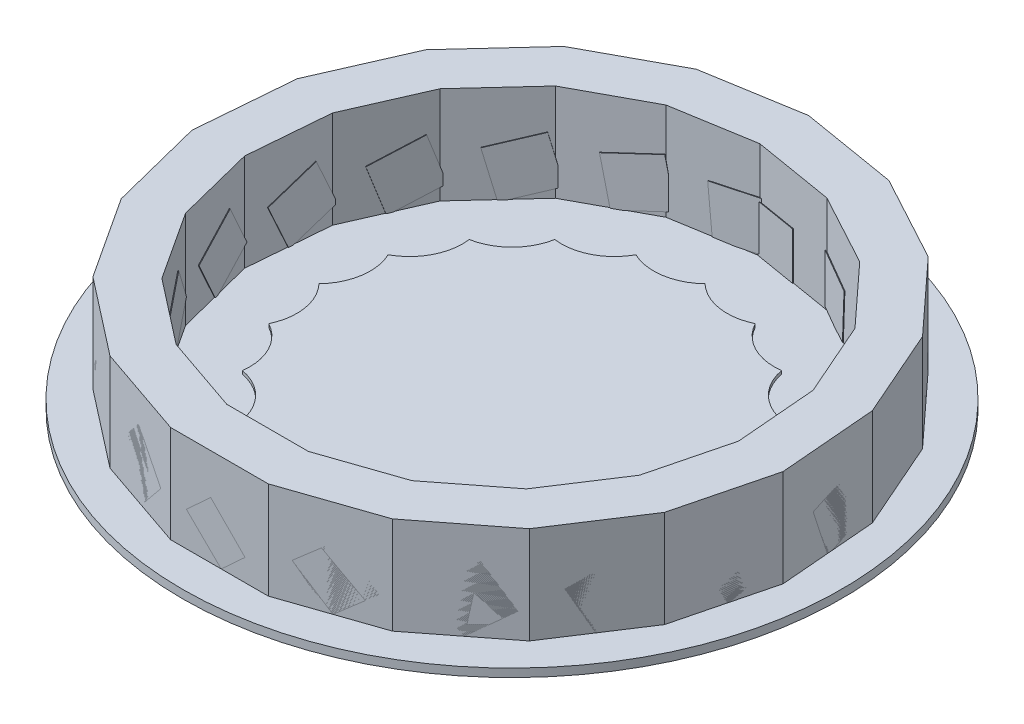
SolidWorks part; units mm, degrees
ref_plane "Front Plane" through (0, 0, 0) normal (0, 0, 1) x (1, 0, 0)
ref_plane "Top Plane" through (0, 0, 0) normal (0, 1, 0) x (1, 0, 0)
ref_plane "Right Plane" through (0, 0, 0) normal (1, 0, 0) x (0, 0, -1)
sketch "Sketch1" plane through (0, 0, 0) normal (0, 1, 0) x (1, 0, 0)
  circle A0 centre (0, 0) radius 100
  circle A1 centre (0, 0) radius 2
  dimension "D1" = 200
  dimension "D2" = 4
extrude "Disk Base" add sketch "Sketch1" along normal blind 2
sketch "Sketch2" plane through (0, 2, 0) normal (0, 1, 0) x (1, 0, 0)
  line L0 (0, 0) -> (0, 90) construction
  line L1 (0, 0) -> (0, 75.19) construction
  line L6 (0, 90) -> (-29.223, 85.1236)
  line L7 (-29.223, 85.1236) -> (-55.2791, 71.0226)
  line L8 (-55.2791, 71.0226) -> (-75.345, 49.2253)
  line L9 (-75.345, 49.2253) -> (-87.246, 22.0937)
  line L10 (-87.246, 22.0937) -> (-89.6926, -7.4321)
  line L11 (-89.6926, -7.4321) -> (-82.4196, -36.1526)
  line L12 (-82.4196, -36.1526) -> (-66.2152, -60.9553)
  line L13 (-66.2152, -60.9553) -> (-42.8353, -79.1526)
  line L14 (-42.8353, -79.1526) -> (-14.8135, -88.7725)
  line L15 (-14.8135, -88.7725) -> (14.8135, -88.7725)
  line L16 (14.8135, -88.7725) -> (42.8353, -79.1526)
  line L17 (42.8353, -79.1526) -> (66.2152, -60.9553)
  line L18 (66.2152, -60.9553) -> (82.4196, -36.1526)
  line L19 (82.4196, -36.1526) -> (89.6926, -7.4321)
  line L20 (89.6926, -7.4321) -> (87.246, 22.0937)
  line L21 (87.246, 22.0937) -> (75.345, 49.2253)
  line L22 (75.345, 49.2253) -> (55.2791, 71.0226)
  line L23 (55.2791, 71.0226) -> (29.223, 85.1236)
  line L24 (29.223, 85.1236) -> (0, 90)
  line L26 (0, 75.19) -> (-24.4142, 71.116)
  line L27 (-24.4142, 71.116) -> (-46.1827, 59.3355)
  line L28 (-46.1827, 59.3355) -> (-62.9465, 41.125)
  line L29 (-62.9465, 41.125) -> (-72.8892, 18.4581)
  line L30 (-72.8892, 18.4581) -> (-74.9332, -6.2091)
  line L31 (-74.9332, -6.2091) -> (-68.857, -30.2035)
  line L32 (-68.857, -30.2035) -> (-55.3191, -50.9248)
  line L33 (-55.3191, -50.9248) -> (-35.7865, -66.1276)
  line L34 (-35.7865, -66.1276) -> (-12.3759, -74.1645)
  line L35 (-12.3759, -74.1645) -> (12.3759, -74.1645)
  line L36 (12.3759, -74.1645) -> (35.7865, -66.1276)
  line L37 (35.7865, -66.1276) -> (55.3191, -50.9248)
  line L38 (55.3191, -50.9248) -> (68.857, -30.2035)
  line L39 (68.857, -30.2035) -> (74.9332, -6.2091)
  line L40 (74.9332, -6.2091) -> (72.8892, 18.4581)
  line L41 (72.8892, 18.4581) -> (62.9465, 41.125)
  line L42 (62.9465, 41.125) -> (46.1827, 59.3355)
  line L43 (46.1827, 59.3355) -> (24.4142, 71.116)
  line L44 (24.4142, 71.116) -> (0, 75.19)
  circle A1 centre (0, 0) radius 88.7725 construction
  circle A2 centre (0, 0) radius 74.1645 construction
  dimension "D1" = 90
  dimension "D2" = 75.19
extrude "Outline" add sketch "Sketch2" along normal blind 30 separate body contours L6 L7 L8 L9 L10 L11 L12 L13 L14 L15 L16 L17 L18 L19 L20 L21 L22 L23 L24 | L26 L27 L28 L29 L30 L31 L32 L33 L34 L35 L36 L37 L38 L39 L40 L41 L42 L43 L44
sketch "Sketch7" plane through (14.6115, 0, -87.5618) normal (0.1646, 0, -0.9864) x (-0.9864, 0, -0.1646)
  line L0 (0, 0) -> (0, 32)
  line L1 (-14.8135, 2) -> (14.8135, 2) construction
  line L2 (0, 2) -> (14.8135, 2)
  line L3 (0, 2) -> (0, 16.81)
  line L4 (0, 16.81) -> (14.8135, 16.81)
  line L5 (14.8135, 2) -> (14.8135, 16.81)
  line L6 (14.8135, 32) -> (14.8135, 2) construction
  line M5 (-14.8135, 2) -> (14.8135, 2)
  dimension "D2" = 14.81
extrude "First Piece" add sketch "Sketch7" against normal blind 14.81 separate body contours L5 L4 L0 M5
sketch "Sketch8" plane through (42.251, 0, -78.0731) normal (0.4759, 0, -0.8795) x (-0.8795, 0, -0.4759)
  line L0 (0, 0) -> (0, 32)
  line L1 (0, 2) -> (-1.223, 16.7594)
  line L2 (-14.8135, 2) -> (14.8135, 2) construction
  line L3 (-1.223, 16.7594) -> (13.5364, 17.9824)
  line L4 (13.5364, 17.9824) -> (14.7594, 3.223)
  line L5 (14.7594, 3.223) -> (0, 2)
  line L6 (100, 2) -> (-100, 2) construction
  dimension "D1" = 14.81
  dimension "D2" = 14.81
  dimension "D3" = 4.737
extrude "Boss-Extrude4" add sketch "Sketch8" against normal blind 14.81 separate body contours L5 L1 L3 L4
sketch "Sketch9" plane through (65.3121, 0, -60.124) normal (0.7357, 0, -0.6773) x (-0.6773, 0, -0.7357)
  line L0 (0, 2) -> (0, 32) construction
  line L1 (-14.8135, 2) -> (14.8135, 2) construction
  line L2 (-14.8135, 32) -> (14.8135, 32) construction
  line L3 (0, 2) -> (-2.4376, 16.608)
  line L4 (-2.4376, 16.608) -> (12.1704, 19.0457)
  line L5 (12.1704, 19.0457) -> (14.608, 4.4376)
  line L6 (14.608, 4.4376) -> (0, 2)
  dimension "D1" = 14.81
  dimension "D2" = 14.81
  dimension "D3" = 9.474
extrude "Boss-Extrude5" add sketch "Sketch9" against normal blind 14.81 separate body
sketch "Sketch10" plane through (81.2955, 0, -35.6595) normal (0.9158, 0, -0.4017) x (-0.4017, 0, -0.9158)
  line L0 (0, 2) -> (0, 32) construction
  line L1 (-14.8135, 2) -> (14.8135, 2) construction
  line L2 (-14.8135, 32) -> (14.8135, 32) construction
  line L3 (0, 2) -> (-3.6356, 16.3568)
  line L4 (-3.6356, 16.3568) -> (10.7212, 19.9925)
  line L5 (10.7212, 19.9925) -> (14.3568, 5.6356)
  line L6 (14.3568, 5.6356) -> (0, 2)
  line L7 (100, 2) -> (-100, 2) construction
  dimension "D1" = 14.81
  dimension "D2" = 14.81
  dimension "D3" = 14.211
extrude "Boss-Extrude6" add sketch "Sketch10" against normal blind 14.81 separate body
sketch "Sketch11" plane through (88.4693, 0, -7.3308) normal (0.9966, 0, -0.0826) x (-0.0826, 0, -0.9966)
  line L0 (0, 0) -> (0, 32) construction
  line L1 (0, 2) -> (-4.8088, 16.0076)
  line L2 (-14.8135, 2) -> (14.8135, 2) construction
  line L3 (-4.8088, 16.0076) -> (9.1988, 20.8164)
  line L4 (9.1988, 20.8164) -> (14.0076, 6.8088)
  line L5 (0, 2) -> (14.0076, 6.8088)
  dimension "D1" = 14.81
  dimension "D2" = 14.81
  dimension "D3" = 18.947
  dimension "D4" = 90
extrude "Boss-Extrude8" add sketch "Sketch11" against normal blind 14.81 separate body
sketch "Sketch12" plane through (86.0561, 0, 21.7924) normal (0.9694, 0, 0.2455) x (0.2455, 0, -0.9694)
  line L0 (0, 2) -> (0, 32) construction
  line L1 (100, 2) -> (-100, 2) construction
  line L2 (-14.8135, 32) -> (14.8135, 32) construction
  line L3 (0, 2) -> (-5.9491, 15.5626)
  line L4 (-5.9491, 15.5626) -> (7.6135, 21.5117)
  line L5 (7.6135, 21.5117) -> (13.5626, 7.9491)
  line L6 (13.5626, 7.9491) -> (0, 2)
  line L7 (-14.8135, 2) -> (14.8135, 2) construction
  dimension "D1" = 14.81
  dimension "D2" = 14.81
  dimension "D3" = 23.684
extrude "Boss-Extrude9" add sketch "Sketch12" against normal blind 14.81 separate body
sketch "Sketch13" plane through (74.3174, 0, 48.554) normal (0.8372, 0, 0.5469) x (0.5469, 0, -0.8372)
  line L0 (0, 2) -> (0, 32) construction
  line L1 (100, 2) -> (-100, 2) construction
  line L2 (-14.8135, 32) -> (14.8135, 32) construction
  line L3 (0, 2) -> (-7.0488, 15.025)
  line L4 (-7.0488, 15.025) -> (5.9762, 22.0738)
  line L5 (5.9762, 22.0738) -> (13.025, 9.0488)
  line L6 (13.025, 9.0488) -> (0, 2)
  dimension "D1" = 14.81
  dimension "D2" = 14.81
  dimension "D3" = 28.421
extrude "Boss-Extrude10" add sketch "Sketch13" against normal blind 14.81 separate body
sketch "Sketch14" plane through (54.5252, 0, 70.054) normal (0.6142, 0, 0.7891) x (0.7891, 0, -0.6142)
  line L0 (0, 2) -> (0, 32) construction
  line L1 (100, 2) -> (-100, 2) construction
  line L2 (-14.8135, 32) -> (14.8135, 32) construction
  line L3 (0, 2) -> (-8.1003, 14.3984)
  line L4 (-8.1003, 14.3984) -> (4.2981, 22.4987)
  line L5 (4.2981, 22.4987) -> (12.3984, 10.1003)
  line L6 (0, 2) -> (12.3984, 10.1003)
  line L7 (-14.8135, 2) -> (14.8135, 2) construction
  dimension "D1" = 14.81
  dimension "D2" = 14.81
  dimension "D3" = 14.81
  dimension "D4" = 33.158
  dimension "D5" = 14.81
extrude "Boss-Extrude11" add sketch "Sketch14" against normal blind 14.81 separate body
sketch "Sketch15" plane through (28.8244, 0, 83.9626) normal (0.3247, 0, 0.9458) x (0.9458, 0, -0.3247)
  line L0 (0, 2) -> (0, 32) construction
  line L1 (100, 2) -> (-100, 2) construction
  line L2 (0, 2) -> (-9.0965, 13.6872)
  line L3 (-9.0965, 13.6872) -> (2.5907, 22.7837)
  line L4 (2.5907, 22.7837) -> (11.6872, 11.0965)
  line L5 (11.6872, 11.0965) -> (0, 2)
  line L6 (-14.8135, 2) -> (14.8135, 2) construction
  dimension "D1" = 14.81
  dimension "D2" = 14.81
  dimension "D3" = 37.895
extrude "Boss-Extrude12" add sketch "Sketch15" against normal blind 14.81 separate body
sketch "Sketch16" plane through (0, 0, 88.7725) normal (0, 0, 1) x (1, 0, 0)
  line L0 (0, 2) -> (0, 32) construction
  line L1 (100, 2) -> (-100, 2) construction
  line L2 (-14.8135, 32) -> (14.8135, 32) construction
  line L3 (0, 2) -> (-10.0305, 12.8961)
  line L4 (-10.0305, 12.8961) -> (0.8655, 22.9266)
  line L5 (0.8655, 22.9266) -> (10.8961, 12.0305)
  line L6 (10.8961, 12.0305) -> (0, 2)
  line L7 (-14.8135, 2) -> (14.8135, 2) construction
  dimension "D1" = 14.81
  dimension "D2" = 14.81
  dimension "D3" = 42.632
extrude "Boss-Extrude13" add sketch "Sketch16" against normal blind 14.81 separate body
sketch "Sketch17" plane through (-28.8244, 0, 83.9626) normal (-0.3247, 0, 0.9458) x (0.9458, 0, 0.3247)
  line L0 (0, 2) -> (0, 32) construction
  line L1 (100, 2) -> (-100, 2) construction
  line L2 (-14.8135, 32) -> (14.8135, 32) construction
  line L3 (0, 2) -> (-10.8961, 12.0305)
  line L4 (-10.8961, 12.0305) -> (-0.8655, 22.9266)
  line L5 (-0.8655, 22.9266) -> (10.0305, 12.8961)
  line L6 (10.0305, 12.8961) -> (0, 2)
  line L7 (-14.8135, 2) -> (14.8135, 2) construction
  dimension "D1" = 14.81
  dimension "D2" = 14.81
  dimension "D3" = 47.368
extrude "10-1" add sketch "Sketch17" against normal blind 14.81 separate body
sketch "Sketch18" plane through (-54.5252, 0, 70.054) normal (-0.6142, 0, 0.7891) x (0.7891, 0, 0.6142)
  line L0 (0, 2) -> (0, 32) construction
  line L1 (100, 2) -> (-100, 2) construction
  line L2 (-14.8135, 32) -> (14.8135, 32) construction
  line L3 (0, 2) -> (-11.6872, 11.0965)
  line L4 (-11.6872, 11.0965) -> (-2.5907, 22.7837)
  line L5 (-2.5907, 22.7837) -> (9.0965, 13.6872)
  line L6 (9.0965, 13.6872) -> (0, 2)
  line L7 (-14.8135, 2) -> (14.8135, 2) construction
  dimension "D1" = 14.81
  dimension "D2" = 14.81
  dimension "D3" = 52.105
extrude "Boss-Extrude15" add sketch "Sketch18" against normal blind 14.81 separate body
sketch "Sketch19" plane through (-74.3174, 0, 48.554) normal (-0.8372, 0, 0.5469) x (0.5469, 0, 0.8372)
  line L0 (0, 2) -> (0, 32) construction
  line L1 (100, 2) -> (-100, 2) construction
  line L2 (-14.8135, 32) -> (14.8135, 32) construction
  line L3 (0, 2) -> (-12.3984, 10.1003)
  line L4 (-12.3984, 10.1003) -> (-4.2981, 22.4987)
  line L5 (-4.2981, 22.4987) -> (8.1003, 14.3984)
  line L6 (0, 2) -> (8.1003, 14.3984)
  dimension "D1" = 14.81
  dimension "D2" = 14.81
  dimension "D3" = 56.842
extrude "Boss-Extrude16" add sketch "Sketch19" against normal blind 14.81 separate body
sketch "Sketch20" plane through (-86.0561, 0, 21.7924) normal (-0.9694, 0, 0.2455) x (0.2455, 0, 0.9694)
  line L0 (0, 2) -> (0, 32) construction
  line L1 (-14.8135, 2) -> (14.8135, 2) construction
  line L2 (-14.8135, 32) -> (14.8135, 32) construction
  line L3 (0, 2) -> (-13.025, 9.0488)
  line L4 (-13.025, 9.0488) -> (-5.9762, 22.0738)
  line L5 (-5.9762, 22.0738) -> (7.0488, 15.025)
  line L6 (7.0488, 15.025) -> (0, 2)
  dimension "D1" = 14.81
  dimension "D2" = 14.81
  dimension "D3" = 14.81
  dimension "D4" = 61.579
extrude "Boss-Extrude17" add sketch "Sketch20" against normal blind 14.81 separate body
sketch "Sketch21" plane through (-88.4693, 0, -7.3308) normal (-0.9966, 0, -0.0826) x (-0.0826, 0, 0.9966)
  line L0 (0, 2) -> (0, 32) construction
  line L1 (100, 2) -> (-100, 2) construction
  line L2 (0, 2) -> (-13.5626, 7.9491)
  line L3 (-13.5626, 7.9491) -> (-7.6135, 21.5117)
  line L4 (-7.6135, 21.5117) -> (5.9491, 15.5626)
  line L5 (5.9491, 15.5626) -> (0, 2)
  line L6 (-14.8135, 2) -> (14.8135, 2) construction
  dimension "D1" = 14.81
  dimension "D2" = 14.81
  dimension "D3" = 66.316
extrude "Boss-Extrude18" add sketch "Sketch21" against normal blind 14.81 separate body
sketch "Sketch22" plane through (-81.2955, 0, -35.6595) normal (-0.9158, 0, -0.4017) x (-0.4017, 0, 0.9158)
  line L0 (0, 2) -> (0, 32) construction
  line L1 (-14.8135, 2) -> (14.8135, 2) construction
  line L2 (-14.8135, 32) -> (14.8135, 32) construction
  line L3 (0, 2) -> (-14.0076, 6.8088)
  line L4 (-14.0076, 6.8088) -> (-9.1988, 20.8164)
  line L5 (-9.1988, 20.8164) -> (4.8088, 16.0076)
  line L6 (4.8088, 16.0076) -> (0, 2)
  dimension "D1" = 14.81
  dimension "D2" = 14.81
  dimension "D3" = 71.053
extrude "Boss-Extrude19" add sketch "Sketch22" against normal blind 14.81 separate body
sketch "Sketch23" plane through (-65.3121, 0, -60.124) normal (-0.7357, 0, -0.6773) x (-0.6773, 0, 0.7357)
  line L0 (0, 2) -> (0, 32) construction
  line L1 (-14.8135, 2) -> (14.8135, 2) construction
  line L2 (-14.8135, 32) -> (14.8135, 32) construction
  line L3 (0, 2) -> (-14.3568, 5.6356)
  line L4 (-14.3568, 5.6356) -> (-10.7212, 19.9925)
  line L5 (-10.7212, 19.9925) -> (3.6356, 16.3568)
  line L6 (3.6356, 16.3568) -> (0, 2)
  dimension "D1" = 14.81
  dimension "D2" = 14.81
  dimension "D3" = 75.789
extrude "Boss-Extrude20" add sketch "Sketch23" against normal blind 14.81 separate body
sketch "Sketch25" plane through (-42.251, 0, -78.0731) normal (-0.4759, 0, -0.8795) x (-0.8795, 0, 0.4759)
  line L0 (0, 2) -> (0, 32) construction
  line L1 (-14.8135, 2) -> (14.8135, 2) construction
  line L2 (-14.8135, 32) -> (14.8135, 32) construction
  line L3 (0, 2) -> (-14.608, 4.4376)
  line L4 (-14.608, 4.4376) -> (-12.1704, 19.0457)
  line L5 (-12.1704, 19.0457) -> (2.4376, 16.608)
  line L6 (2.4376, 16.608) -> (0, 2)
  line L7 (100, 2) -> (-100, 2) construction
  dimension "D1" = 14.81
  dimension "D2" = 14.81
  dimension "D3" = 80.526
extrude "Boss-Extrude21" add sketch "Sketch25" against normal blind 14.81 separate body
sketch "Sketch26" plane through (-14.6115, 0, -87.5618) normal (-0.1646, 0, -0.9864) x (-0.9864, 0, 0.1646)
  line L0 (0, 2) -> (0, 32) construction
  line L1 (-14.8135, 2) -> (14.8135, 2) construction
  line L2 (-14.8135, 32) -> (14.8135, 32) construction
  line L3 (0, 2) -> (-14.7594, 3.223)
  line L4 (-14.7594, 3.223) -> (-13.5364, 17.9824)
  line L5 (-13.5364, 17.9824) -> (1.223, 16.7594)
  line L6 (1.223, 16.7594) -> (0, 2)
  dimension "D1" = 14.81
  dimension "D2" = 14.81
  dimension "D3" = 85.263
extrude "Boss-Extrude22" add sketch "Sketch26" against normal blind 14.81 separate body
sketch "Sketch27" plane through (0, 2, 0) normal (0, 1, 0) x (1, 0, 0)
  circle A0 centre (0, 0) radius 100
  circle A1 centre (0, 0) radius 2
extrude "Boss-Extrude23" add sketch "Sketch27" along normal blind 0.5
sketch "Sketch28" plane through (0, 2.5, 0) normal (0, 1, 0) x (1, 0, 0)
  line L0 (0, 0) -> (0, 117.1406) construction
  line L1 (0, 0) -> (36.1985, 111.4074) construction
  line L2 (0, 0) -> (68.8535, 94.7688) construction
  line L3 (0, 0) -> (94.7688, 68.8535) construction
  line L4 (0, 0) -> (111.4074, 36.1985) construction
  line L5 (0, 0) -> (117.1406, 0) construction
  line L6 (0, 0) -> (111.4074, -36.1985) construction
  line L7 (0, 0) -> (94.7688, -68.8535) construction
  line L8 (0, 0) -> (68.8535, -94.7688) construction
  line L9 (0, 0) -> (36.1985, -111.4074) construction
  line L10 (0, 0) -> (0, -117.1406) construction
  line L11 (0, 0) -> (-36.1985, -111.4074) construction
  line L12 (0, 0) -> (-68.8535, -94.7688) construction
  line L13 (0, 0) -> (-94.7688, -68.8535) construction
  line L14 (0, 0) -> (-111.4074, -36.1985) construction
  line L15 (0, 0) -> (-117.1406, 0) construction
  line L16 (0, 0) -> (-111.4074, 36.1985) construction
  line L17 (0, 0) -> (-94.7688, 68.8535) construction
  line L18 (0, 0) -> (-68.8535, 94.7688) construction
  line L19 (0, 0) -> (-36.1985, 111.4074) construction
  circle A0 centre (0, 0) radius 55 construction
  circle A1 centre (0, 0) radius 42.5 construction
  arc A2 (0, 58.5703) -> (-18.0992, 55.7037) centre (-11.1314, 70.2806) cw
  arc A3 (18.0992, 55.7037) -> (0, 58.5703) centre (11.1314, 70.2806) cw
  arc A4 (34.4268, 47.3844) -> (18.0992, 55.7037) centre (32.3045, 63.4011) cw
  arc A5 (47.3844, 34.4268) -> (34.4268, 47.3844) centre (50.3154, 50.3154) cw
  arc A6 (55.7037, 18.0992) -> (47.3844, 34.4268) centre (63.4011, 32.3045) cw
  arc A7 (58.5703, 0) -> (55.7037, 18.0992) centre (70.2806, 11.1314) cw
  arc A8 (55.7037, -18.0992) -> (58.5703, 0) centre (70.2806, -11.1314) cw
  arc A9 (47.3844, -34.4268) -> (55.7037, -18.0992) centre (63.4011, -32.3045) cw
  arc A10 (34.4268, -47.3844) -> (47.3844, -34.4268) centre (50.3154, -50.3154) cw
  arc A11 (18.0992, -55.7037) -> (34.4268, -47.3844) centre (32.3045, -63.4011) cw
  arc A12 (0, -58.5703) -> (18.0992, -55.7037) centre (11.1314, -70.2806) cw
  arc A13 (-18.0992, -55.7037) -> (0, -58.5703) centre (-11.1314, -70.2806) cw
  arc A14 (-34.4268, -47.3844) -> (-18.0992, -55.7037) centre (-32.3045, -63.4011) cw
  arc A15 (-47.3844, -34.4268) -> (-34.4268, -47.3844) centre (-50.3154, -50.3154) cw
  arc A16 (-55.7037, -18.0992) -> (-47.3844, -34.4268) centre (-63.4011, -32.3045) cw
  arc A17 (-58.5703, 0) -> (-55.7037, -18.0992) centre (-70.2806, -11.1314) cw
  arc A18 (-55.7037, 18.0992) -> (-58.5703, 0) centre (-70.2806, 11.1314) cw
  arc A19 (-47.3844, 34.4268) -> (-55.7037, 18.0992) centre (-63.4011, 32.3045) cw
  arc A20 (-34.4268, 47.3844) -> (-47.3844, 34.4268) centre (-50.3154, 50.3154) cw
  arc A21 (-18.0992, 55.7037) -> (-34.4268, 47.3844) centre (-32.3045, 63.4011) cw
  point P25 (0, 0)
  point P88 (0, 0)
  dimension "D2" = 110
  dimension "D3" = 85
  dimension "D1" = 20
  dimension "D4" = 20
extrude "Boss-Extrude24" add sketch "Sketch28" along normal blind 1 contours A2 A21 A20 A19 A18 A17 A16 A15 A14 A13 A12 A11 A10 A9 A8 A7 A6 A5 A4 A3
